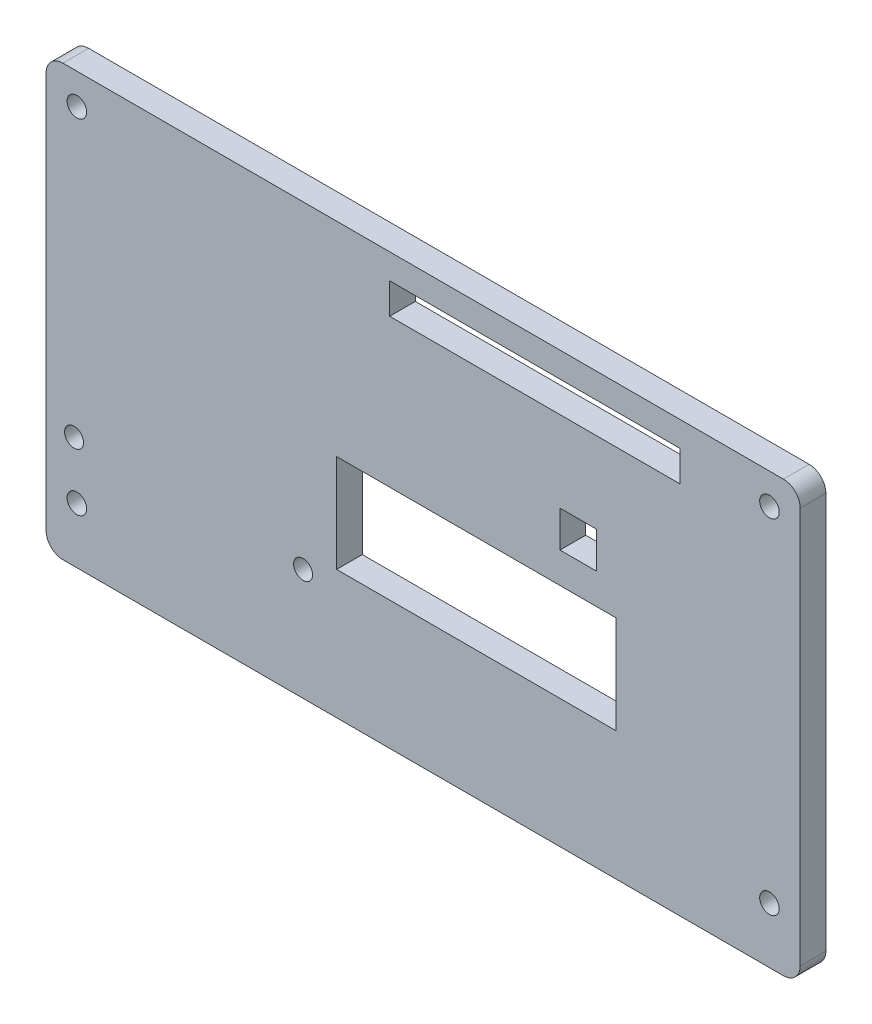
SolidWorks part; units mm, degrees
ref_plane "Front Plane" through (0, 0, 0) normal (0, 0, 1) x (1, 0, 0)
ref_plane "Top Plane" through (0, 0, 0) normal (0, 1, 0) x (1, 0, 0)
ref_plane "Right Plane" through (0, 0, 0) normal (1, 0, 0) x (0, 0, -1)
sketch "Sketch1" plane through (0, 0, 0) normal (0, 0, 1) x (1, 0, 0)
  line L0 (7.9248, 82.036) -> (136.9248, 82.036)
  line L1 (139.9248, 79.036) -> (139.9248, 8.036)
  line L2 (136.9248, 5.036) -> (7.9248, 5.036)
  line L3 (4.9248, 8.036) -> (4.9248, 79.036)
  line L4 (66.4248, 77.536) -> (118.4248, 77.536)
  line L5 (118.4248, 77.536) -> (118.4248, 72.036)
  line L6 (118.4248, 72.036) -> (66.4248, 72.036)
  line L7 (66.4248, 72.036) -> (66.4248, 77.536)
  line L8 (56.9248, 45.536) -> (106.9248, 45.536)
  line L9 (106.9248, 45.536) -> (106.9248, 28.036)
  line L10 (106.9248, 28.036) -> (56.9248, 28.036)
  line L11 (56.9248, 28.036) -> (56.9248, 45.536)
  line L12 (96.9248, 57.536) -> (103.4248, 57.536)
  line L13 (103.4248, 57.536) -> (103.4248, 51.036)
  line L14 (103.4248, 51.036) -> (96.9248, 51.036)
  line L15 (96.9248, 51.036) -> (96.9248, 57.536)
  line L16 (10.4248, 15.036) -> (134.4248, 15.036) construction
  line L17 (134.4248, 15.036) -> (134.4248, 76.536) construction
  arc A0 (139.9248, 79.036) -> (136.9248, 82.036) centre (136.9248, 79.036) ccw
  arc A1 (136.9248, 5.036) -> (139.9248, 8.036) centre (136.9248, 8.036) ccw
  arc A2 (4.9248, 8.036) -> (7.9248, 5.036) centre (7.9248, 8.036) ccw
  arc A3 (7.9248, 82.036) -> (4.9248, 79.036) centre (7.9248, 79.036) ccw
  circle A4 centre (134.4248, 76.536) radius 1.75
  circle A5 centre (10.4248, 76.536) radius 1.75
  circle A6 centre (10.4248, 15.036) radius 1.75
  circle A7 centre (134.4248, 15.036) radius 1.75
  dimension "D1" = 3.5
extrude "Extrude1" add sketch "Sketch1" along normal blind 4.6
sketch "Sketch2" plane through (0, 0, 0) normal (0, 0, -1) x (-1, 0, 0)
  line L0 (-9.9248, 25.036) -> (-50.9248, 25.036) construction
  line L1 (-4.9248, 79.036) -> (-4.9248, 8.036) construction
  line L2 (-7.9248, 5.036) -> (-136.9248, 5.036) construction
  circle A0 centre (-50.9248, 25.036) radius 1.7
  circle A1 centre (-9.9248, 25.036) radius 1.7
  dimension "D4" = 3.4
  dimension "D5" = 3.4
  dimension "D1" = 41
  dimension "D2" = 5
  dimension "D3" = 20
extrude "Cut-Extrude1" cut sketch "Sketch2" against normal through all
